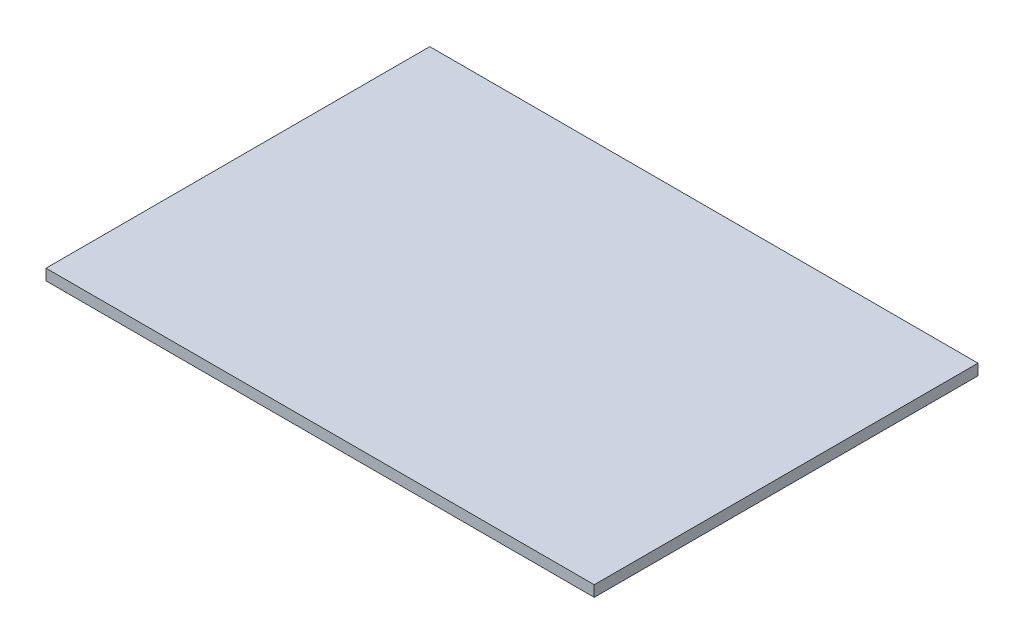
SolidWorks part; units mm, degrees
ref_plane "Front Plane" through (0, 0, 0) normal (0, 0, 1) x (1, 0, 0)
ref_plane "Top Plane" through (0, 0, 0) normal (0, 1, 0) x (1, 0, 0)
ref_plane "Right Plane" through (0, 0, 0) normal (1, 0, 0) x (0, 0, -1)
sketch "Sketch1" plane through (0, 0, 0) normal (0, 1, 0) x (1, 0, 0)
  line L1 (-50, -35) -> (50, -35)
  line L2 (-50, -35) -> (-50, 35)
  line L3 (-50, 35) -> (50, 35)
  line L4 (50, -35) -> (50, 35)
  line L5 (-50, -35) -> (50, 35) construction
  line L6 (-50, 35) -> (50, -35) construction
  point P0 (0, 0)
  dimension "D1" = 100
  dimension "D2" = 70
extrude "Boss-Extrude1" add sketch "Sketch1" along normal blind 2
sketch "Sketch2" plane through (0, 2, 0) normal (0, 1, 0) x (1, 0, 0)
  line L0 (34.533, -39) -> (34.533, -36) construction
  line L1 (34.533, -36) -> (44.533, -36) construction
  line L2 (44.533, -36) -> (44.533, -39) construction
  line L3 (44.533, -39) -> (34.533, -39) construction
  line L4 (-43.967, -39) -> (-43.967, -36) construction
  line L5 (-43.967, -36) -> (33.033, -36) construction
  line L6 (-21.967, 19) -> (-21.967, -9)
  line L7 (46.533, 19) -> (-21.967, 19)
  line L8 (46.533, -36) -> (46.533, 19)
  line L9 (-46.967, -36) -> (46.533, -36)
  line L10 (-46.967, -9) -> (-46.967, -36)
  line L11 (-21.967, -9) -> (-46.967, -9)
  line L12 (-21.967, 19) -> (-21.967, -9)
  line L13 (46.533, 19) -> (-21.967, 19)
  line L14 (46.533, -36) -> (46.533, 19)
  line L15 (-46.967, -36) -> (46.533, -36)
  line L16 (-46.967, -9) -> (-46.967, -36)
  line L17 (-21.967, -9) -> (-46.967, -9)
  line L18 (33.033, -36) -> (33.033, -39) construction
  line L19 (33.033, -39) -> (-43.967, -39) construction
  line L20 (34.533, -39) -> (34.533, -36)
  line L21 (34.533, -36) -> (44.533, -36)
  line L22 (44.533, -36) -> (44.533, -39)
  line L23 (44.533, -39) -> (34.533, -39)
  line L24 (-43.967, -39) -> (-43.967, -36)
  line L25 (-43.967, -36) -> (33.033, -36)
  line L26 (33.033, -36) -> (33.033, -39)
  line L27 (33.033, -39) -> (-43.967, -39)
  dimension "D1" = 0
